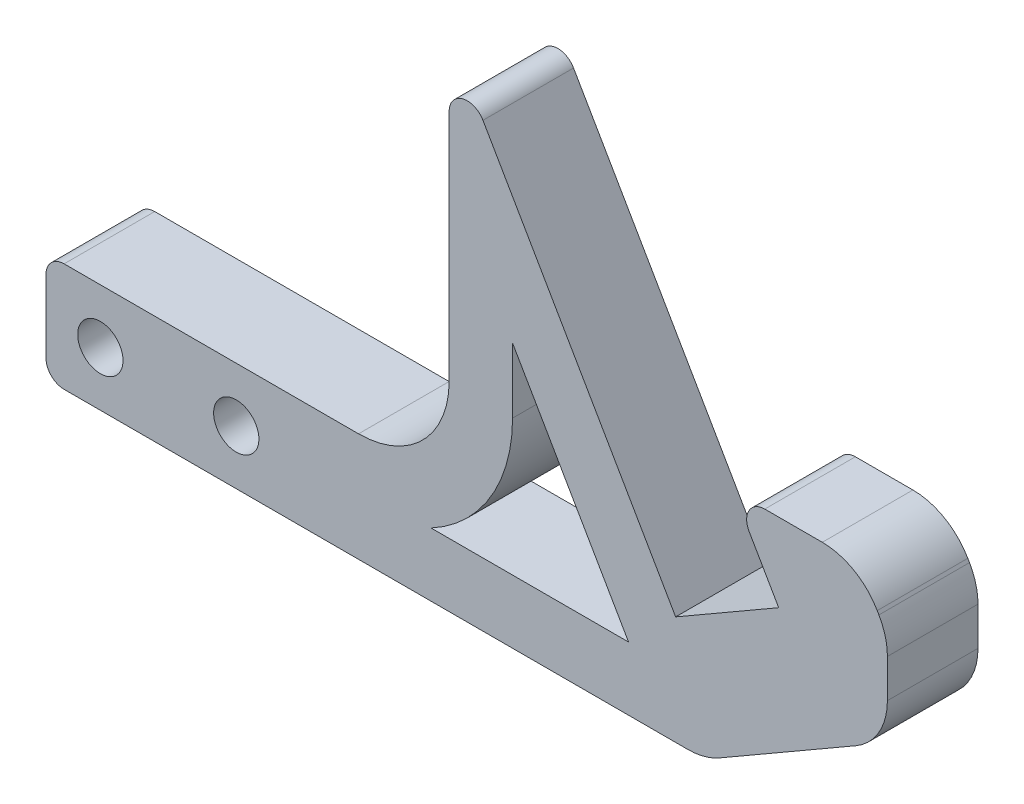
SolidWorks part; units mm, degrees
ref_plane "Front Plane" through (0, 0, 0) normal (0, 0, 1) x (1, 0, 0)
ref_plane "Top Plane" through (0, 0, 0) normal (0, 1, 0) x (1, 0, 0)
ref_plane "Right Plane" through (0, 0, 0) normal (1, 0, 0) x (0, 0, -1)
sketch "Sketch1" plane through (0, 0, 0) normal (0, 0, 1) x (1, 0, 0)
  line L0 (-11.5266, 6) -> (20.9734, 6)
  line L12 (57.3132, -6) -> (-11.5266, -6)
  line L13 (-13.5266, -4) -> (-13.5266, 4)
  line L14 (-7.5266, 0) -> (7.4734, 0) construction
  line L15 (11.4734, 6) -> (11.4734, -6) construction
  line L16 (67.3489, 12.5677) -> (64.081, 18.2279)
  line L17 (67.3489, 12.5677) -> (55.9734, 6)
  line L19 (78.2261, 17.7279) -> (78.4111, 17.4074)
  line L20 (75.8489, 3.6187) -> (60.8132, -5.0622)
  line L21 (55.9734, 6) -> (34.7055, 42.8372)
  line L22 (30.9734, 41.8372) -> (30.9734, 16)
  line L23 (65.813, 21.2279) -> (72.1639, 21.2279)
  line L24 (79.3489, 13.9074) -> (79.3489, 9.6809)
  line L25 (50.7773, 1) -> (50.7773, 1)
  line L26 (50.7773, 1) -> (50.7773, 1)
  line L27 (50.7773, 1) -> (50.7773, 1)
  line L28 (50.7773, 1) -> (28.9734, 1)
  line L29 (28.9734, 1) -> (28.9734, 1)
  line L30 (28.9734, 1) -> (28.9734, 1)
  line L31 (37.9734, 23.1769) -> (37.9734, 16)
  line L32 (50.7773, 1) -> (37.9734, 23.1769)
  line L33 (50.7773, 1) -> (50.7773, 1)
  line L34 (50.7773, 1) -> (50.7773, 1)
  line L35 (50.7773, 1) -> (50.7773, 1)
  circle A0 centre (-7.5266, 0) radius 2.5
  circle A1 centre (7.4734, 0) radius 2.5
  arc A2 (30.9734, 16) -> (20.9734, 6) centre (20.9734, 16) cw
  arc A3 (34.7055, 42.8372) -> (30.9734, 41.8372) centre (32.9734, 41.8372) ccw
  arc A4 (60.8132, -5.0622) -> (57.3132, -6) centre (57.3132, 1) cw
  arc A5 (79.3489, 9.6809) -> (75.8489, 3.6187) centre (72.3489, 9.6809) cw
  arc A6 (79.3489, 13.9074) -> (78.4111, 17.4074) centre (72.3489, 13.9074) ccw
  arc A7 (72.1639, 21.2279) -> (78.2261, 17.7279) centre (72.1639, 14.2279) cw
  arc A8 (64.081, 18.2279) -> (65.813, 21.2279) centre (65.813, 19.2279) cw
  arc A9 (-11.5266, -6) -> (-13.5266, -4) centre (-11.5266, -4) cw
  arc A10 (-11.5266, 6) -> (-13.5266, 4) centre (-11.5266, 4) ccw
  arc A11 (50.7773, 1) -> (50.7773, 1) centre (50.7773, 1) ccw
  arc A12 (50.7773, 1) -> (50.7773, 1) centre (50.7773, 1) cw
  arc A13 (50.7773, 1) -> (50.7773, 1) centre (50.7773, 1) cw
  arc A14 (28.9734, 1) -> (28.9734, 1) centre (28.9734, 1) cw
  arc A15 (28.9734, 1) -> (28.9734, 1) centre (28.9734, 1) ccw
  arc A16 (37.9734, 16) -> (28.9734, 1) centre (20.9734, 16) cw
  arc A17 (37.9734, 23.1769) -> (37.9734, 23.1769) centre (37.9734, 23.1769) ccw
  arc A18 (50.7773, 1) -> (50.7773, 1) centre (50.7773, 1) cw
  arc A19 (50.7773, 1) -> (50.7773, 1) centre (50.7773, 1) cw
  point P17 (0, 0)
  point P33 (62.3489, 21.2279)
  dimension "D1" = 5
  dimension "D3" = 6
  dimension "D4" = 6
  dimension "D5" = 15
  dimension "D6" = 4
  dimension "D19" = 10
  dimension "D20" = 2
  dimension "D21" = 7
  dimension "D22" = 2
  dimension "D23" = 2
  dimension "D2" = 12
  dimension "D7" = 90
  dimension "D8" = 12
  dimension "D9" = 60
  dimension "D10" = 12
  dimension "D11" = 13.1353
  dimension "D12" = 55.9734
  dimension "D13" = 10
  dimension "D14" = 13.5266
  dimension "D15" = 60
  dimension "D16" = 25
  dimension "D17" = 12
  dimension "D18" = 27.2279
  dimension "D24" = 7
extrude "Boss-Extrude1" add sketch "Sketch1" along normal blind 10
